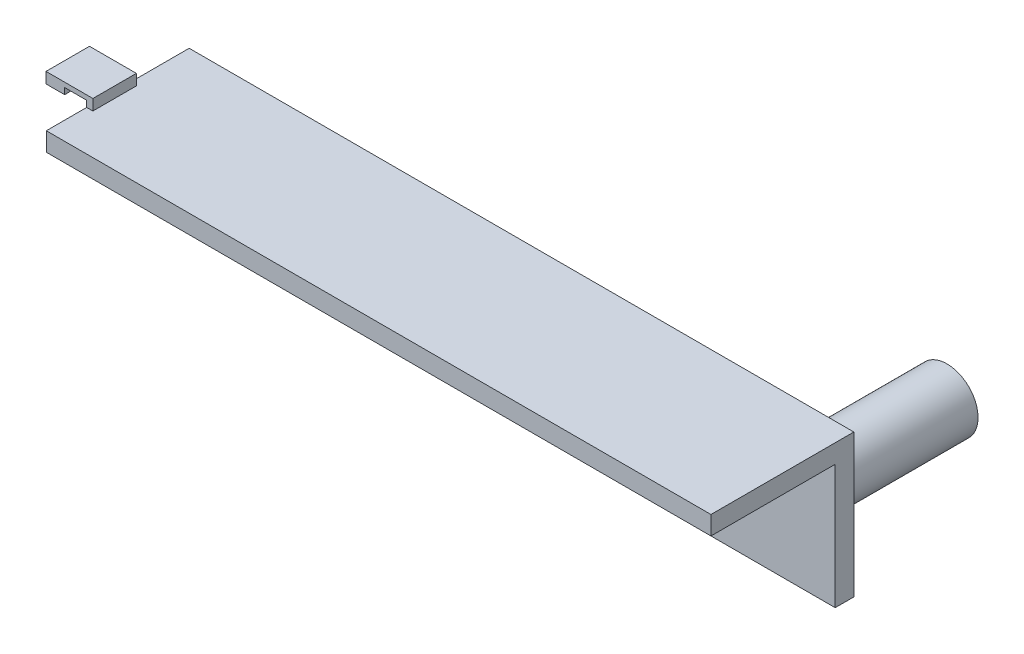
SolidWorks part; units mm, degrees
ref_plane "Front Plane" through (0, 0, 0) normal (0, 0, 1) x (1, 0, 0)
ref_plane "Top Plane" through (0, 0, 0) normal (0, 1, 0) x (1, 0, 0)
ref_plane "Right Plane" through (0, 0, 0) normal (1, 0, 0) x (0, 0, -1)
sketch "Sketch1" plane through (0, 0, 0) normal (0, 0, 1) x (1, 0, 0)
  line L1 (0, 0) -> (20, 0)
  line L2 (0, 0) -> (0, -23)
  line L3 (0, -23) -> (20, -23)
  line L4 (20, 0) -> (20, -23)
  dimension "D1" = 20
  dimension "D2" = 23
extrude "Boss-Extrude1" add sketch "Sketch1" along normal blind 3 contours L2 L3 L4 L1
sketch "Sketch2" plane through (0, 0, 3) normal (0, 0, 1) x (1, 0, 0)
  line L0 (20, 0) -> (20, -23) construction
  line L1 (0, 0) -> (20, 0)
  line L2 (0, 0) -> (0, -3)
  line L3 (0, -3) -> (20, -3)
  line L4 (20, 0) -> (20, -3)
  dimension "D1" = 3
extrude "Boss-Extrude2" add sketch "Sketch2" along normal blind 20
sketch "Sketch3" plane through (0, 0, 0) normal (0, 0, -1) x (-1, 0, 0)
  line L0 (0, -23) -> (-20, -23) construction
  line L3 (0, 0) -> (0, -23) construction
  circle A0 centre (-10, -13) radius 5
  dimension "D1" = 10
  dimension "D2" = 10
  dimension "D3" = 10
extrude "Boss-Extrude3" add sketch "Sketch3" along normal blind 25
sketch "Sketch4" plane through (0, 0, -25) normal (0, 0, -1) x (-1, 0, 0)
  line L0 (0, 0) -> (0, -23) construction
  line L2 (0, -23) -> (-20, -23) construction
  circle A0 centre (-10, -13) radius 3
  dimension "D1" = 6
  dimension "D2" = 10
  dimension "D3" = 10
extrude "Cut-Extrude1" cut sketch "Sketch4" against normal blind 25
sketch "Sketch5" plane through (0, 0, 0) normal (-1, 0, 0) x (0, 0, 1)
  line L1 (0, 0) -> (23, 0)
  line L2 (0, 0) -> (0, -3)
  line L3 (0, -3) -> (23, -3)
  line L4 (23, 0) -> (23, -3)
extrude "Boss-Extrude4" add sketch "Sketch5" along normal blind 87
sketch "Sketch6" plane through (0, 0, 0) normal (0, 1, 0) x (1, 0, 0)
  line L0 (-87, 0) -> (20, 0) construction
  circle A0 centre (-82.9, -11.5) radius 2.5
  dimension "D1" = 5
  dimension "D2" = 82.9
  dimension "D3" = 11.5
sketch "Sketch8" plane through (0, 0, 0) normal (0, 0, 1) x (1, 0, 0)
  line L0 (-87, 0) -> (-87, 1)
  line L1 (-86.5761, 0) -> (-86.5761, 1) construction
  line L2 (-90.55, 1.75) -> (-93.55, 1.75)
  line L3 (-86, 1.75) -> (-86, 0)
  line L4 (20, 0) -> (-87, 0) construction
  line L5 (-86.5761, 1) -> (-87, 1) construction
  line L6 (-93.55, 1.75) -> (-93.55, 0)
  line L7 (-90.55, 1) -> (-90.55, 0)
  line L8 (-90.55, 1.75) -> (-86, 1.75)
  line L9 (-90.55, 1) -> (-87, 1)
  line L10 (-90.55, 0) -> (-93.55, 0)
  line L15 (-87, 0) -> (-86, 0)
  dimension "D1" = 1
  dimension "D2" = 1
  dimension "D3" = 3
  dimension "D4" = 3.55
  dimension "D5" = 0.75
extrude "Boss-Extrude5" add sketch "Sketch8" along normal blind 5 and the other way blind 2 from vertex at 11.5 starting at point (-82.9, 0, 11.5)
